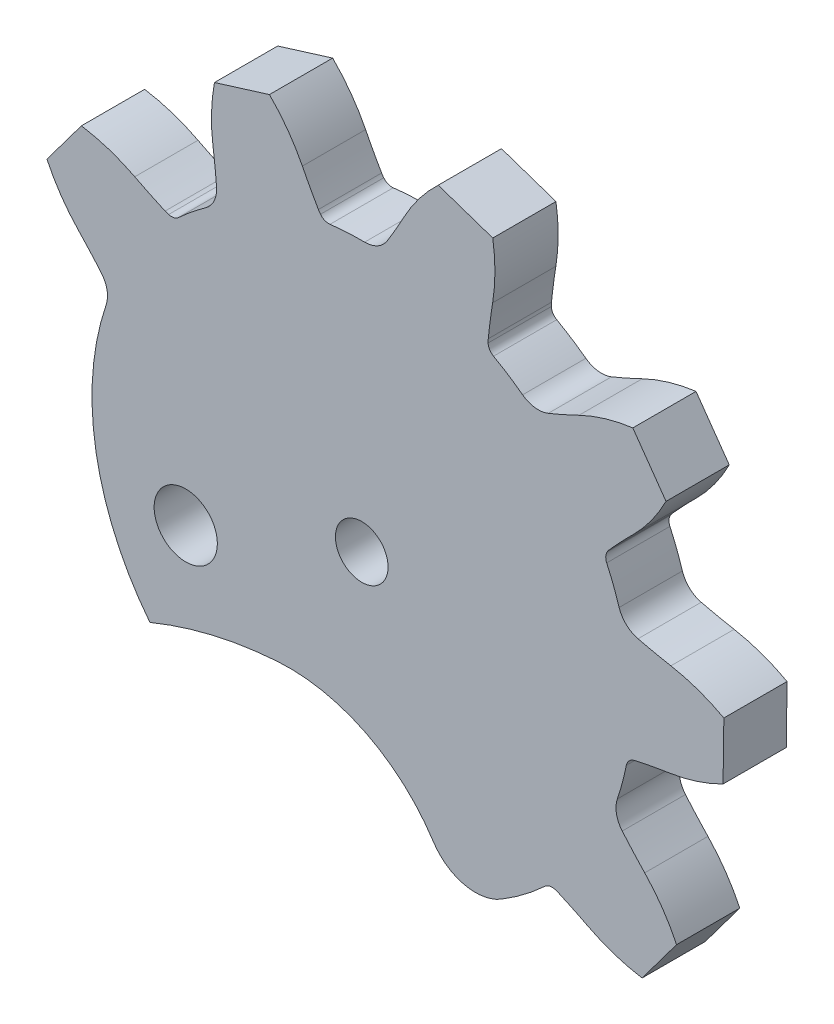
SolidWorks part; units mm, degrees
ref_plane "Front Plane" through (0, 0, 0) normal (0, 0, 1) x (1, 0, 0)
ref_plane "Top Plane" through (0, 0, 0) normal (0, 1, 0) x (1, 0, 0)
ref_plane "Right Plane" through (0, 0, 0) normal (1, 0, 0) x (0, 0, -1)
sketch "Sketch1" plane through (0, 0, 0) normal (0, 0, 1) x (1, 0, 0)
  line L0 (0.9337, 0.8311) -> (9.6237, -8.567) construction
  line L5 (10.0986, -8.4529) -> (0.9337, 0.8311) construction
  line L6 (0.9337, 0.8311) -> (13.0641, -3.2548) construction
  line L7 (0.9337, 0.8311) -> (13.2948, -4.4592) construction
  line L8 (18.0794, -0.1345) -> (18.1164, 2.5971)
  line L9 (15.3724, 10.1279) -> (13.7968, 12.3596)
  line L10 (7.1503, 16.8393) -> (4.5639, 17.7186)
  line L11 (-3.4463, 17.436) -> (-6.0556, 16.6271)
  line L12 (-12.3699, 11.6902) -> (-14.0054, 9.5021)
  line L14 (-7.4181, -2.2568) -> (0.9337, 0.8311) construction
  line L15 (0.9337, 0.8311) -> (7.4057, 0.6948) construction
  line L17 (14.2374, -10.0281) -> (15.8729, -7.84)
  arc A1 (-9.1183, -7.0935) -> (-11.1967, 4.917) centre (0.9337, 0.8311) cw
  arc A2 (13.0641, -3.2548) -> (13.4881, -1.6643) centre (0.9337, 0.8311) ccw construction
  arc A3 (13.8052, -1.2928) -> (13.4881, -1.6643) centre (13.9785, -1.7618) ccw
  arc A4 (13.975, -1.2434) -> (13.8052, -1.2928) centre (14.2373, -2.4623) ccw
  arc A5 (15.5436, -0.9539) -> (13.975, -1.2434) centre (19.6718, -27.7126) ccw
  arc A6 (15.5436, -0.9539) -> (18.0794, -0.1345) centre (14.2642, 7.339) ccw
  arc A7 (18.1164, 2.5971) -> (15.6038, 3.4849) centre (14.1002, -4.7703) ccw
  arc A8 (14.0435, 3.8168) -> (15.6038, 3.4849) centre (20.4554, 30.1219) ccw
  arc A9 (13.149, 4.6556) -> (14.0435, 3.8168) centre (14.3388, 5.0281) ccw
  arc A10 (12.5954, 6.6785) -> (12.5572, 6.1916) centre (13.0112, 6.401) ccw
  arc A11 (12.7037, 6.8182) -> (12.5954, 6.6785) centre (13.6323, 5.9864) ccw
  arc A12 (13.8025, 7.9745) -> (12.7037, 6.8182) centre (32.8707, -11.2472) ccw
  arc A13 (13.8025, 7.9745) -> (15.3724, 10.1279) centre (7.8931, 13.9316) ccw
  arc A14 (13.7968, 12.3596) -> (11.2422, 11.6009) centre (14.878, 4.0385) ccw
  arc A15 (9.7848, 10.9523) -> (11.2422, 11.6009) centre (-0.4896, 36.0024) ccw
  arc A16 (8.5681, 11.1051) -> (9.7848, 10.9523) centre (9.3117, 12.1058) ccw
  arc A17 (6.9311, 12.4163) -> (7.1865, 11.9999) centre (7.4307, 12.4362) ccw
  arc A18 (6.9366, 12.593) -> (6.9311, 12.4163) centre (8.1769, 12.4658) ccw
  arc A19 (7.146, 14.1744) -> (6.9366, 12.593) centre (33.8707, 9.8316) ccw
  arc A20 (7.146, 14.1744) -> (7.1503, 16.8393) centre (-1.1363, 15.5202) ccw
  arc A21 (4.5639, 17.7186) -> (2.9431, 15.6032) centre (10.3296, 11.6222) ccw
  arc A22 (2.1453, 14.2219) -> (2.9431, 15.6032) centre (-20.891, 28.4487) ccw
  arc A23 (1.0711, 13.6303) -> (2.1453, 14.2219) centre (1.0845, 14.877) ccw
  arc A24 (-1.0239, 13.7289) -> (-0.5726, 13.5421) centre (-0.6314, 14.0387) ccw
  arc A25 (-1.1233, 13.8751) -> (-1.0239, 13.7289) centre (-0.0452, 14.5012) ccw
  arc A26 (-1.8834, 15.2775) -> (-1.1233, 13.8751) centre (22.2899, 27.4726) ccw
  arc A27 (-1.8834, 15.2775) -> (-3.4463, 17.436) centre (-9.3751, 11.4981) ccw
  arc A28 (-6.0556, 16.6271) -> (-6.1235, 13.9631) centre (2.1923, 15.0841) ccw
  arc A29 (-5.957, 12.3766) -> (-6.1235, 13.9631) centre (-32.9561, 10.346) ccw
  arc A30 (-6.4783, 11.2667) -> (-5.957, 12.3766) centre (-7.2003, 12.2831) ccw
  arc A31 (-8.2312, 10.115) -> (-7.7563, 10.2292) centre (-8.0957, 10.5963) ccw
  arc A32 (-8.3975, 10.1749) -> (-8.2312, 10.115) centre (-7.8933, 11.3151) ccw
  arc A33 (-9.8368, 10.8626) -> (-8.3975, 10.1749) centre (2.5518, 34.9374) ccw
  arc A34 (-9.8368, 10.8626) -> (-12.3699, 11.6902) centre (-13.6762, 3.4015) ccw
  arc A35 (-14.0054, 9.5021) -> (-12.4945, 7.307) centre (-6.4258, 13.1017) ccw
  arc A36 (-11.4273, 6.1213) -> (-12.4945, 7.307) centre (-32.0764, -11.3911) ccw
  arc A37 (-11.1967, 4.917) -> (-11.4273, 6.1213) centre (-12.3782, 5.3149) ccw
  arc A38 (-7.7563, 10.2292) -> (-6.4783, 11.2667) centre (0.9337, 0.8311) cw
  arc A39 (-0.5726, 13.5421) -> (1.0711, 13.6303) centre (0.9337, 0.8311) cw
  arc A40 (7.1865, 11.9999) -> (8.5681, 11.1051) centre (0.9337, 0.8311) cw
  arc A41 (12.5572, 6.1916) -> (13.149, 4.6556) centre (0.9337, 0.8311) cw
  arc A42 (13.4881, -1.6643) -> (13.0641, -3.2548) centre (0.9337, 0.8311) cw
  circle A47 centre (-7.4181, -2.2568) radius 1.5
  circle A49 centre (0.9337, 0.8311) radius 1.25
  arc A113 (-3.0855, -5.6707) -> (-9.1183, -7.0935) centre (-1.7537, -24.8192) ccw
  arc A114 (4.3379, -9.3844) -> (-3.0855, -5.6707) centre (-2.5191, -13.8147) ccw
  arc A115 (4.3379, -9.3844) -> (7.5587, -10.1272) centre (6.3309, -8.0967) ccw
  arc A116 (7.5587, -10.1272) -> (9.6237, -8.567) centre (1.0592, 0.6218) ccw
  arc A117 (10.0986, -8.4529) -> (9.6237, -8.567) centre (9.9631, -8.9341) ccw
  arc A118 (10.265, -8.5127) -> (10.0986, -8.4529) centre (9.7608, -9.6529) ccw
  arc A119 (11.7042, -9.2005) -> (10.265, -8.5127) centre (-0.6844, -33.2752) ccw
  arc A120 (11.7042, -9.2005) -> (14.2374, -10.0281) centre (15.5436, -1.7394) ccw
  arc A121 (15.8729, -7.84) -> (14.3619, -5.6448) centre (8.2932, -11.4396) ccw
  arc A122 (13.2948, -4.4592) -> (14.3619, -5.6448) centre (33.9438, 13.0533) ccw
  arc A123 (13.0641, -3.2548) -> (13.2948, -4.4592) centre (14.2456, -3.6528) ccw
  point P112 (0.9337, 0.8311)
  dimension "D2" = 8.1636
  dimension "D3" = 2.3728
  dimension "D4" = 0.5
  dimension "D5" = 1.2468
  dimension "D7" = 1.2468
  dimension "D8" = 27.0753
  dimension "D9" = 8.391
  dimension "D1" = 19.1948
  dimension "D6" = 27.0753
  dimension "D10" = 8.391
  dimension "D12" = 12.5612
  dimension "D13" = 6
  dimension "D24" = 2.5
  dimension "D26" = 3
  dimension "D27" = 0.244
  dimension "D11" = 2.7318
  dimension "D14" = 4.555
  dimension "D15" = 22.2
  dimension "D16" = 1.872
  dimension "D19" = 8.9044
  dimension "D22" = 17.409
extrude "Boss-Extrude1" add sketch "Sketch1" along normal blind 3 contours A123 A42 A3 A4 A5 A6 L8 A7 A8 A9 A41 A10 A11 A12 A13 L9 A14 A15 A16 A40 A17 A18 A19 A20 L10 A21 A22 A23 A39 A24 A25 A26 A27 L11 A28 A29 A30 A38 A31 A32 A33 A34 L12 A35 A36 A37 A1 A113 A114 A115 A116
